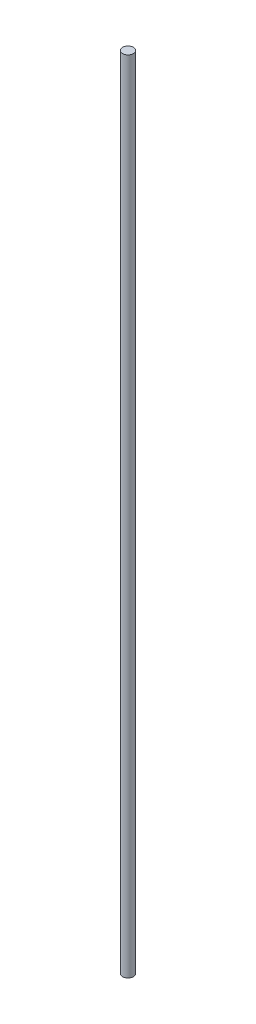
SolidWorks part; units mm, degrees
ref_plane "Front Plane" through (0, 0, 0) normal (0, 0, 1) x (1, 0, 0)
ref_plane "Top Plane" through (0, 0, 0) normal (0, 1, 0) x (1, 0, 0)
ref_plane "Right Plane" through (0, 0, 0) normal (1, 0, 0) x (0, 0, -1)
sketch "Sketch1" plane through (0, 0, 0) normal (0, 1, 0) x (1, 0, 0)
  circle A0 centre (0, 0) radius 4.1
  dimension "D1" = 8.2
extrude "Boss-Extrude1" add sketch "Sketch1" along normal blind 600
